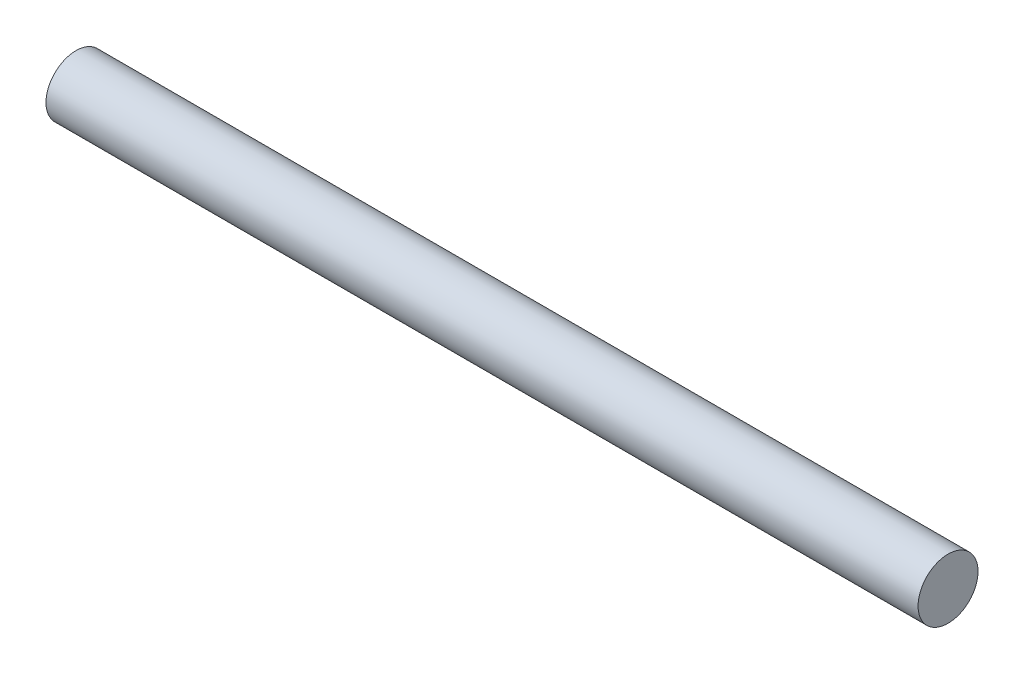
SolidWorks part; units mm, degrees
ref_plane "Front Plane" through (0, 0, 0) normal (0, 0, 1) x (1, 0, 0)
ref_plane "Top Plane" through (0, 0, 0) normal (0, 1, 0) x (1, 0, 0)
ref_plane "Right Plane" through (0, 0, 0) normal (1, 0, 0) x (0, 0, -1)
sketch "Sketch1" plane through (0, 0, 0) normal (1, 0, 0) x (0, 0, -1)
  circle A0 centre (0, 0) radius 0.9975
  dimension "D1" = 1.995
extrude "Boss-Extrude1" add sketch "Sketch1" along normal blind 29
